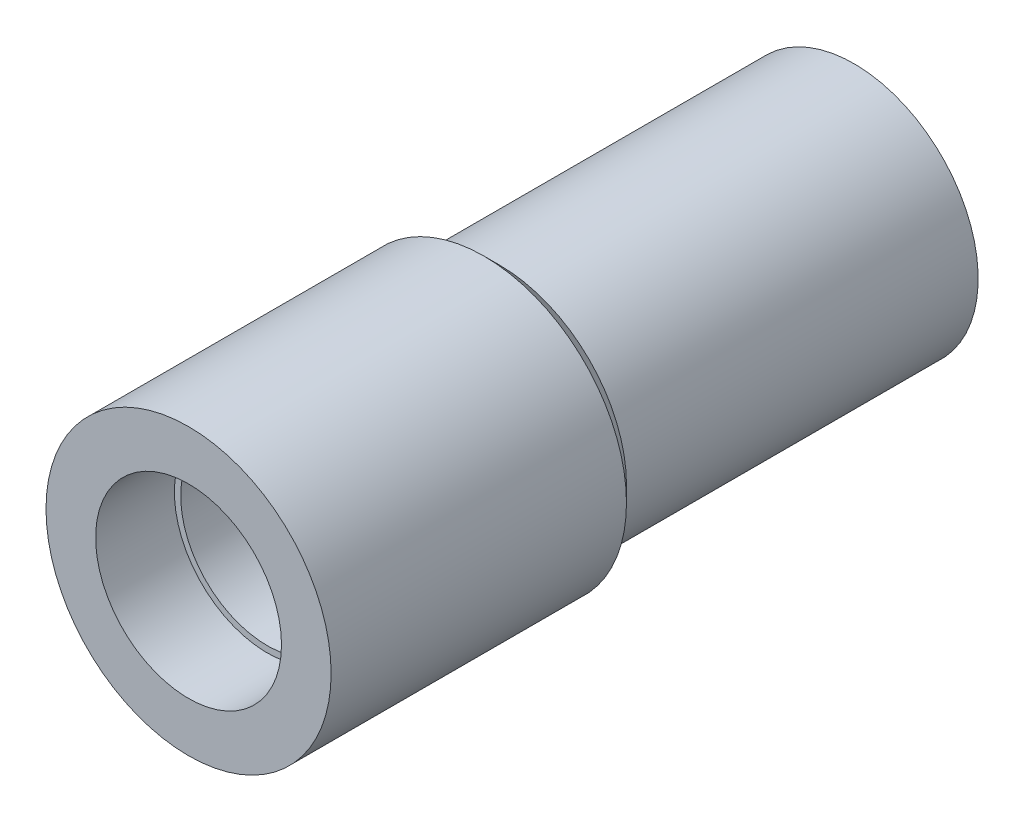
SolidWorks part; units mm, degrees
ref_plane "Front Plane" through (0, 0, 0) normal (0, 0, 1) x (1, 0, 0)
ref_plane "Top Plane" through (0, 0, 0) normal (0, 1, 0) x (1, 0, 0)
ref_plane "Right Plane" through (0, 0, 0) normal (1, 0, 0) x (0, 0, -1)
sketch "Sketch1" plane through (0, 0, 0) normal (0, 0, 1) x (1, 0, 0)
  circle A0 centre (0, 0) radius 4.5974
extrude "Extrude1" add sketch "Sketch1" along normal blind 21.463
sketch "Sketch3" plane through (0, 0, 21.463) normal (0, 0, 1) x (1, 0, 0)
  circle A0 centre (0, 0) radius 2.794
extrude "Cut-Extrude2" cut sketch "Sketch3" against normal through all
sketch "Sketch4" plane through (0, 0, 21.463) normal (0, 0, 1) x (1, 0, 0)
  circle A0 centre (0, 0) radius 2.9972
extrude "Cut-Extrude3" cut sketch "Sketch4" against normal blind 2.54
sketch "Sketch5" plane through (0, 0, 0) normal (0, 0, -1) x (-1, 0, 0)
  circle A0 centre (0, 0) radius 4.0005
extrude "Cut-Extrude4" cut sketch "Sketch5" against normal blind 11.43 flip side to cut
sketch "Sketch6" plane through (0, 0, 0) normal (0, 0, -1) x (-1, 0, 0)
  circle A0 centre (0, 0) radius 2.9972
extrude "Cut-Extrude5" cut sketch "Sketch6" against normal blind 2.54
chamfer "Chamfer1" distance 0.508 angle 45 1 edges at (-4.5974, 0, 11.43)
